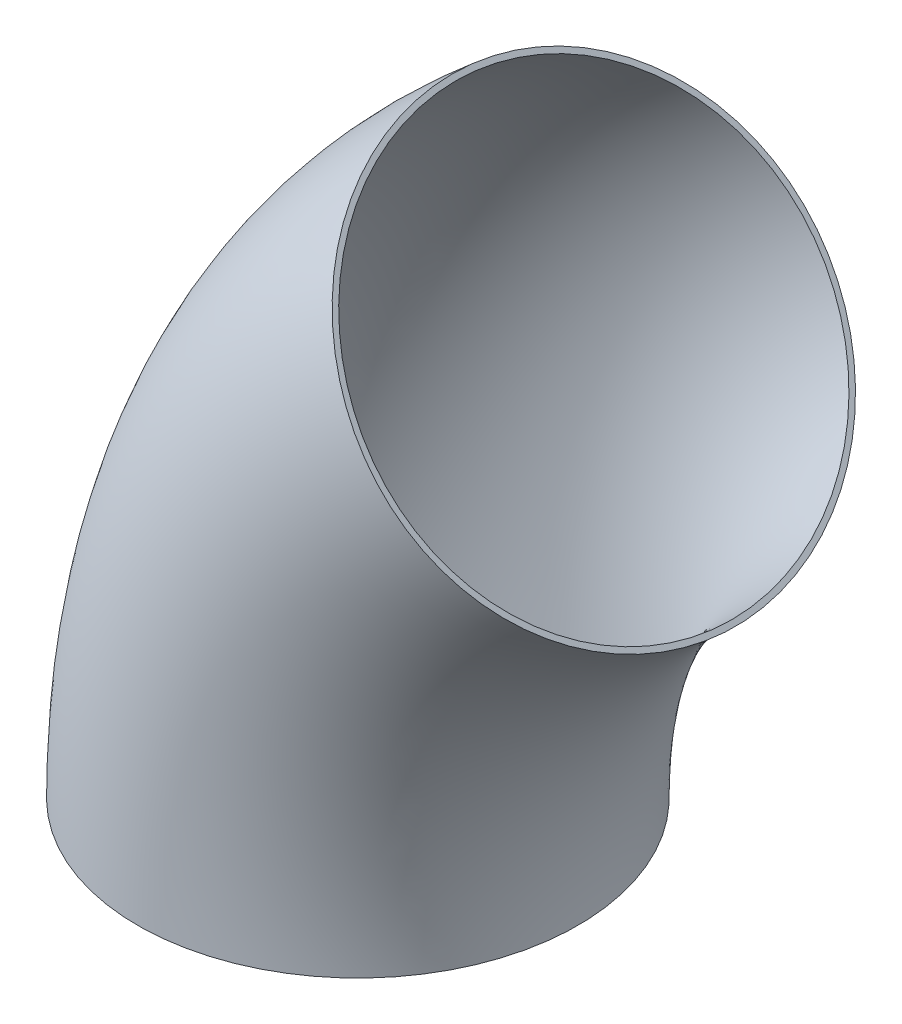
SolidWorks part; units mm, degrees
material "AISI 304"
ref_plane "Piano frontale" through (0, 0, 0) normal (0, 0, 1) x (1, 0, 0)
ref_plane "Piano superiore" through (0, 0, 0) normal (0, 1, 0) x (1, 0, 0)
ref_plane "Piano destro" through (0, 0, 0) normal (1, 0, 0) x (0, 0, -1)
sketch "Schizzo1" plane through (0, 0, 0) normal (0, 0, 1) x (1, 0, 0)
  line L0 (0, 0) -> (-103.6024, 123.4686) construction
  line L1 (0, 0) -> (-182.2917, 0) construction
  arc A4 (-77.1345, 91.9253) -> (-120, 0) centre (0, 0) ccw
  point P1 (0, 0)
sketch "Schizzo3" plane through (0, 0, 0) normal (0, 1, 0) x (1, 0, 0)
  line L0 (0, 0) -> (-182.2917, 0) construction
  circle A0 centre (-120.0502, 0) radius 40
sweep "Sweep-Sottile1" add profiles "Schizzo3" path "Schizzo1" parameters "D1"=1
